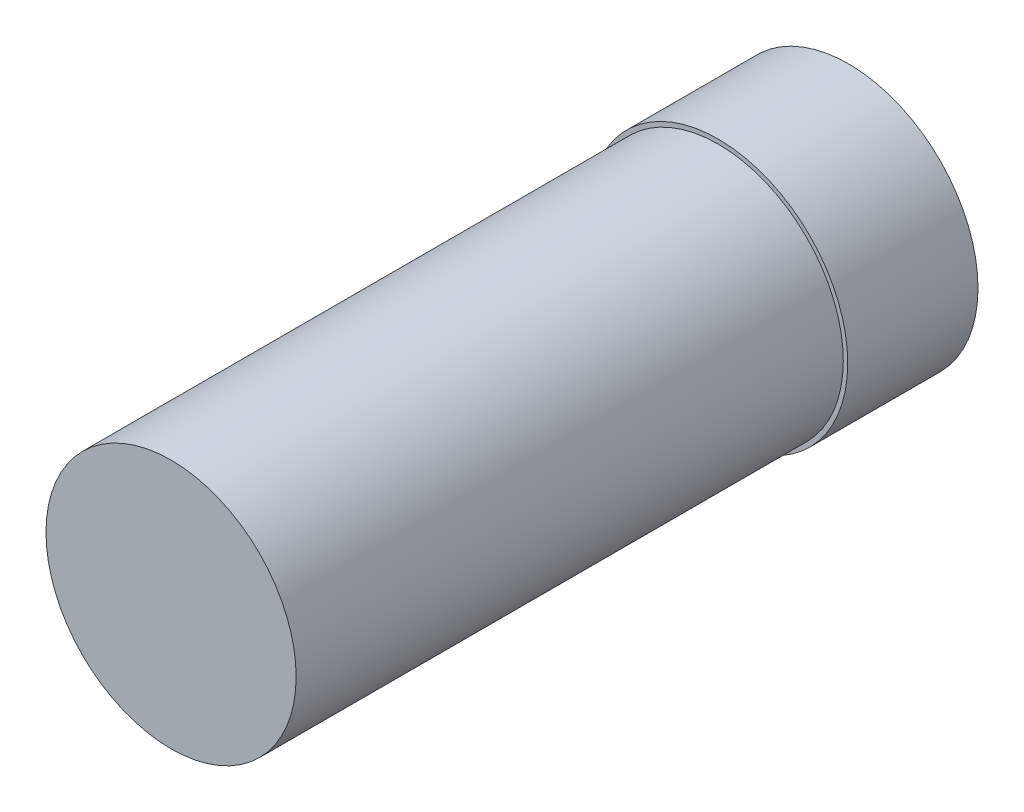
SolidWorks part; units mm, degrees
ref_plane "정면" through (0, 0, 0) normal (0, 0, 1) x (1, 0, 0)
ref_plane "윗면" through (0, 0, 0) normal (0, 1, 0) x (1, 0, 0)
ref_plane "우측면" through (0, 0, 0) normal (1, 0, 0) x (0, 0, -1)
sketch "스케치1" plane through (0, 0, 0) normal (0, 0, 1) x (1, 0, 0)
  circle A0 centre (0, 0) radius 2.485
  dimension "D1" = 4.97
extrude "보스-돌출1" add sketch "스케치1" along normal blind 2.5
sketch "스케치2" plane through (0, 0, 2.5) normal (0, 0, 1) x (1, 0, 0)
  circle A0 centre (0, 0) radius 2.4
  dimension "D1" = 4.8
extrude "보스-돌출2" add sketch "스케치2" along normal blind 10.5
sketch "스케치3" plane through (0, 0, 13) normal (0, 0, 1) x (1, 0, 0)
  circle A0 centre (0, 0) radius 2.45
  dimension "D1" = 4.9
